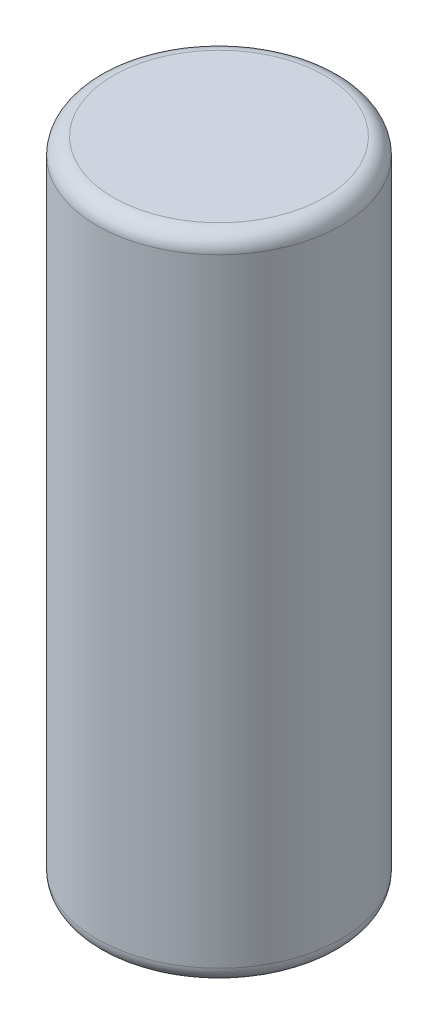
SolidWorks part; units mm, degrees
material "Carbon Fiber"
ref_plane "Front Plane" through (0, 0, 0) normal (0, 0, 1) x (1, 0, 0)
ref_plane "Top Plane" through (0, 0, 0) normal (0, 1, 0) x (1, 0, 0)
ref_plane "Right Plane" through (0, 0, 0) normal (1, 0, 0) x (0, 0, -1)
sketch "Sketch1" plane through (0, 0, 0) normal (0, 1, 0) x (1, 0, 0)
  line L2 (0, -55) -> (0, 55) construction
  circle A1 centre (0, 0) radius 75
  dimension "D1" = 150
extrude "Boss-Extrude1" add sketch "Sketch1" along normal mid plane 400
fillet "Fillet1" radius 10 2 edges at (0, 200, 75) (0, -200, 75)
